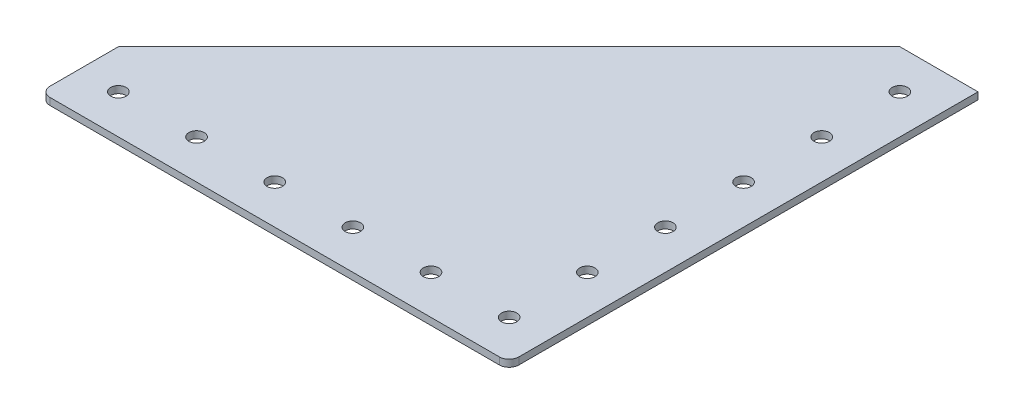
SolidWorks part; units mm, degrees
ref_plane "Front Plane" through (0, 0, 0) normal (0, 0, 1) x (1, 0, 0)
ref_plane "Top Plane" through (0, 0, 0) normal (0, 1, 0) x (1, 0, 0)
ref_plane "Right Plane" through (0, 0, 0) normal (1, 0, 0) x (0, 0, -1)
sketch "Sketch1" plane through (0, 0, 0) normal (0, 1, 0) x (1, 0, 0)
  line L0 (0, 0) -> (0, 152.4)
  line L1 (0, 152.4) -> (-25.4, 152.4)
  line L2 (-25.4, 152.4) -> (-152.4, 25.4)
  line L3 (-152.4, 25.4) -> (-152.4, 0)
  line L4 (-152.4, 0) -> (0, 0)
  circle A0 centre (-12.7, 12.7) radius 2.4892
  circle A1 centre (-38.1, 12.7) radius 2.4892
  circle A2 centre (-63.5, 12.7) radius 2.4892
  circle A3 centre (-88.9, 12.7) radius 2.4892
  circle A4 centre (-114.3, 12.7) radius 2.4892
  circle A5 centre (-12.7, 38.1) radius 2.4892
  circle A6 centre (-12.7, 63.5) radius 2.4892
  circle A7 centre (-12.7, 88.9) radius 2.4892
  circle A8 centre (-12.7, 114.3) radius 2.4892
  circle A9 centre (-139.7, 12.7) radius 2.4892
  circle A13 centre (-12.7, 139.7) radius 2.4892
  dimension "D4" = 12.7
  dimension "D5" = 12.7
  dimension "D1" = 152.4
  dimension "D2" = 25.4
  dimension "D3" = 152.4
  dimension "D10" = 25.4
  dimension "D6" = 6
  dimension "D7" = 6
extrude "Boss-Extrude2" add sketch "Sketch1" along normal mid plane 2.286
fillet "Fillet1" radius 3.175 2 edges at (0, 0, 0) (-152.4, 0, 0)
